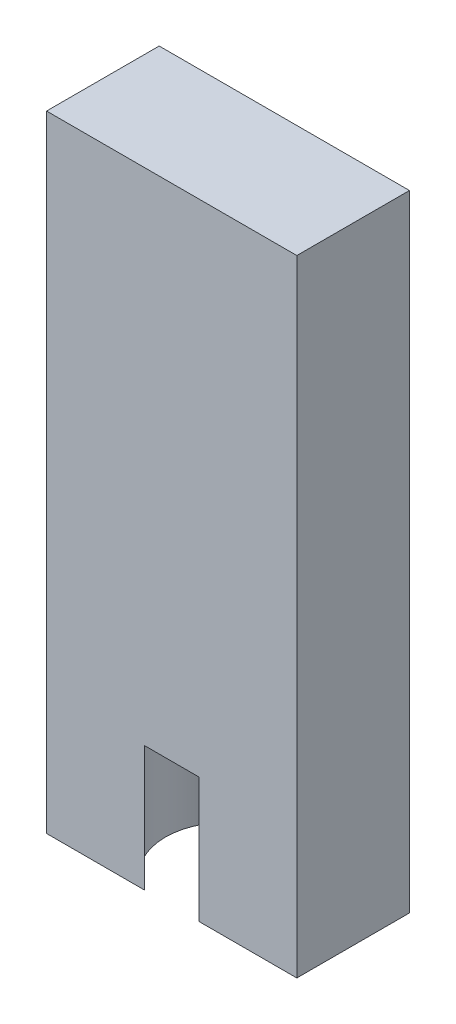
SolidWorks part; units mm, degrees
ref_plane "Front Plane" through (0, 0, 0) normal (0, 0, 1) x (1, 0, 0)
ref_plane "Top Plane" through (0, 0, 0) normal (0, 1, 0) x (1, 0, 0)
ref_plane "Right Plane" through (0, 0, 0) normal (1, 0, 0) x (0, 0, -1)
sketch "Sketch1" plane through (0, 0, 0) normal (0, 1, 0) x (1, 0, 0)
  line L1 (-20, 9) -> (20, 9)
  line L2 (-20, 9) -> (-20, -9)
  line L3 (-20, -9) -> (20, -9)
  line L4 (20, 9) -> (20, -9)
  line L5 (-20, 9) -> (20, -9) construction
  line L6 (-20, -9) -> (20, 9) construction
  point P0 (0, 0)
  dimension "D1" = 40
  dimension "D2" = 18
extrude "Boss-Extrude1" add sketch "Sketch1" along normal blind 100
sketch "Sketch3" plane through (0, 0, 0) normal (0, -1, 0) x (1, 0, 0)
  circle A0 centre (0, 0) radius 10
  circle A1 centre (0, 22) radius 5
  circle A2 centre (0, -22) radius 5
  dimension "D1" = 20
  dimension "D2" = 10
  dimension "D3" = 10
  dimension "D4" = 22
  dimension "D5" = 22
extrude "Cut-Extrude2" cut sketch "Sketch3" against normal blind 20
sketch "Sketch6" plane through (0, 100, 0) normal (0, 1, 0) x (1, 0, 0)
  line L0 (-20, -9) -> (20, -9) construction
  line L1 (-20, 9) -> (20, 9)
  line L2 (-20, 9) -> (-20, -9)
  line L3 (-20, -9) -> (20, -9)
  line L4 (20, 9) -> (20, -9)
  line L5 (-20, 9) -> (20, -9) construction
  line L6 (-20, -9) -> (20, 9) construction
  line L7 (20, -9) -> (20, 9) construction
  point P0 (0, 0)
